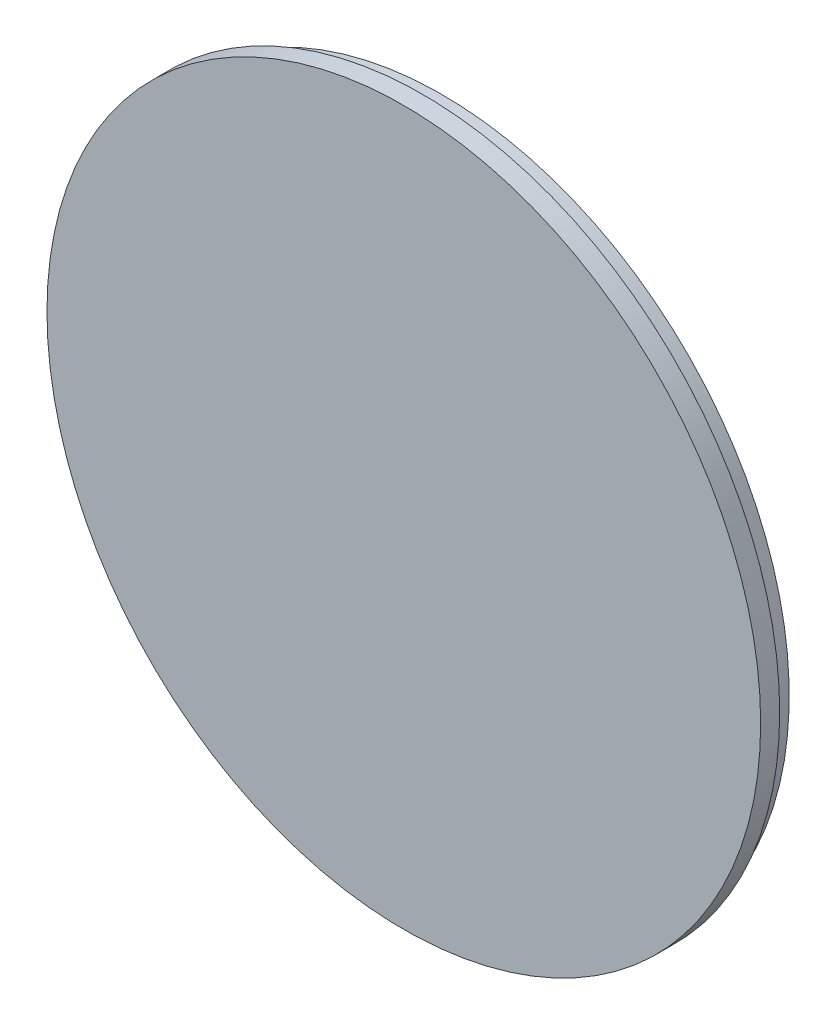
SolidWorks part; units mm, degrees
ref_plane "Front Plane" through (0, 0, 0) normal (0, 0, 1) x (1, 0, 0)
ref_plane "Top Plane" through (0, 0, 0) normal (0, 1, 0) x (1, 0, 0)
ref_plane "Right Plane" through (0, 0, 0) normal (1, 0, 0) x (0, 0, -1)
sketch "Sketch1" plane through (0, 0, 0) normal (0, 0, 1) x (1, 0, 0)
  circle A0 centre (0, 0) radius 18.75
  dimension "D1" = 37.5
extrude "Boss-Extrude1" add sketch "Sketch1" along normal blind 1
sketch "Sketch2" plane through (0, 0, 0) normal (0, 0, -1) x (-1, 0, 0)
  circle A0 centre (0, 0) radius 18.25
  dimension "D1" = 36.5
extrude "Boss-Extrude2" add sketch "Sketch2" along normal blind 1
